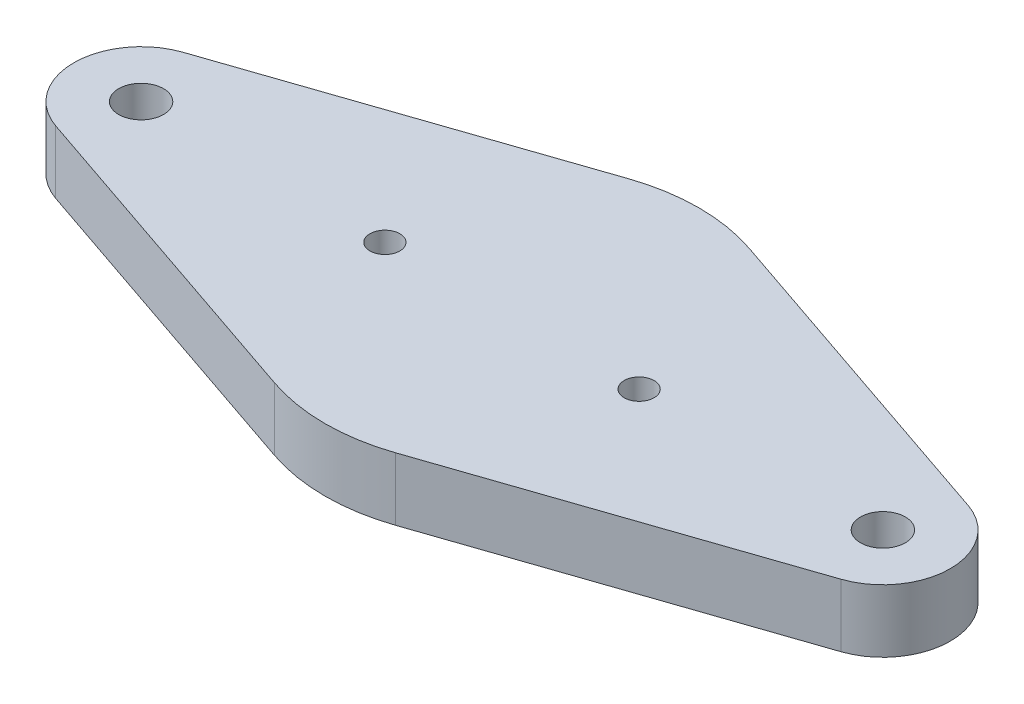
SolidWorks part; units mm, degrees
ref_plane "Alzado" through (0, 0, 0) normal (0, 0, 1) x (1, 0, 0)
ref_plane "Planta" through (0, 0, 0) normal (0, 1, 0) x (1, 0, 0)
ref_plane "Vista lateral" through (0, 0, 0) normal (1, 0, 0) x (0, 0, -1)
sketch "Croquis1" plane through (0, 0, 0) normal (0, 1, 0) x (1, 0, 0)
  line L0 (26.2516, 4.2594) -> (4.0323, 11.8318)
  line L1 (-4.0323, 11.8318) -> (-26.2516, 4.2594)
  line L2 (-4.0323, -11.8318) -> (-26.2516, -4.2594)
  line L3 (26.2516, -4.2594) -> (4.0323, -11.8318)
  line L4 (0, 12.5) -> (0, -12.5) construction
  arc A0 (-4.0323, -11.8318) -> (4.0323, -11.8318) centre (0, 0) ccw
  arc A1 (26.2516, -4.2594) -> (26.2516, 4.2594) centre (24.8, 0) ccw
  arc A2 (-26.2516, 4.2594) -> (-26.2516, -4.2594) centre (-24.8, 0) ccw
  arc A3 (4.0323, 11.8318) -> (-4.0323, 11.8318) centre (0, 0) ccw
  circle A4 centre (24.8, 0) radius 1.5
  circle A5 centre (-24.8, 0) radius 1.5
  circle A6 centre (8.5, 0) radius 1
  circle A7 centre (-8.5, 0) radius 1
  dimension "D1" = 25
  dimension "D2" = 9
  dimension "D5" = 3
  dimension "D6" = 2
  dimension "D3" = 49.6
  dimension "D4" = 24.8
  dimension "D7" = 17
  dimension "D8" = 8.5
extrude "Saliente-Extruir1" add sketch "Croquis1" along normal blind 4.2
